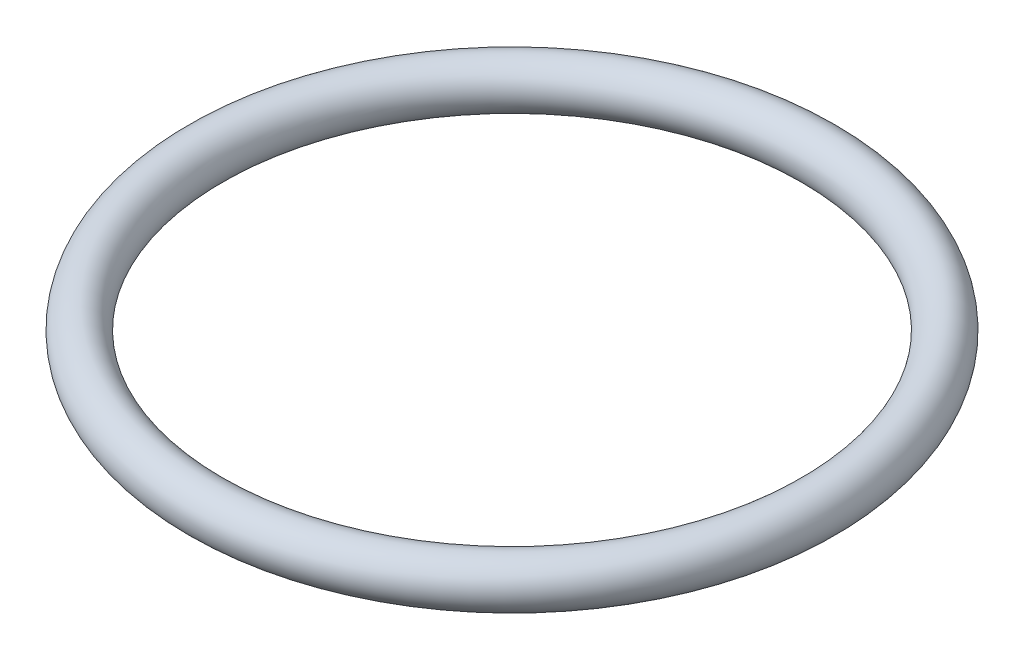
SolidWorks part; units mm, degrees
ref_plane "Front Plane" through (0, 0, 0) normal (0, 0, 1) x (1, 0, 0)
ref_plane "Top Plane" through (0, 0, 0) normal (0, 1, 0) x (1, 0, 0)
ref_plane "Right Plane" through (0, 0, 0) normal (1, 0, 0) x (0, 0, -1)
sketch "Sketch1" plane through (0, 0, 0) normal (0, 0, 1) x (1, 0, 0)
  line L0 (0, 0) -> (0, 6.5518) construction
  circle A0 centre (13, 0) radius 1
  dimension "D1" = 2
  dimension "D2" = 13
revolve "Revolve1" add sketch "Sketch1" angle 360 about L0
